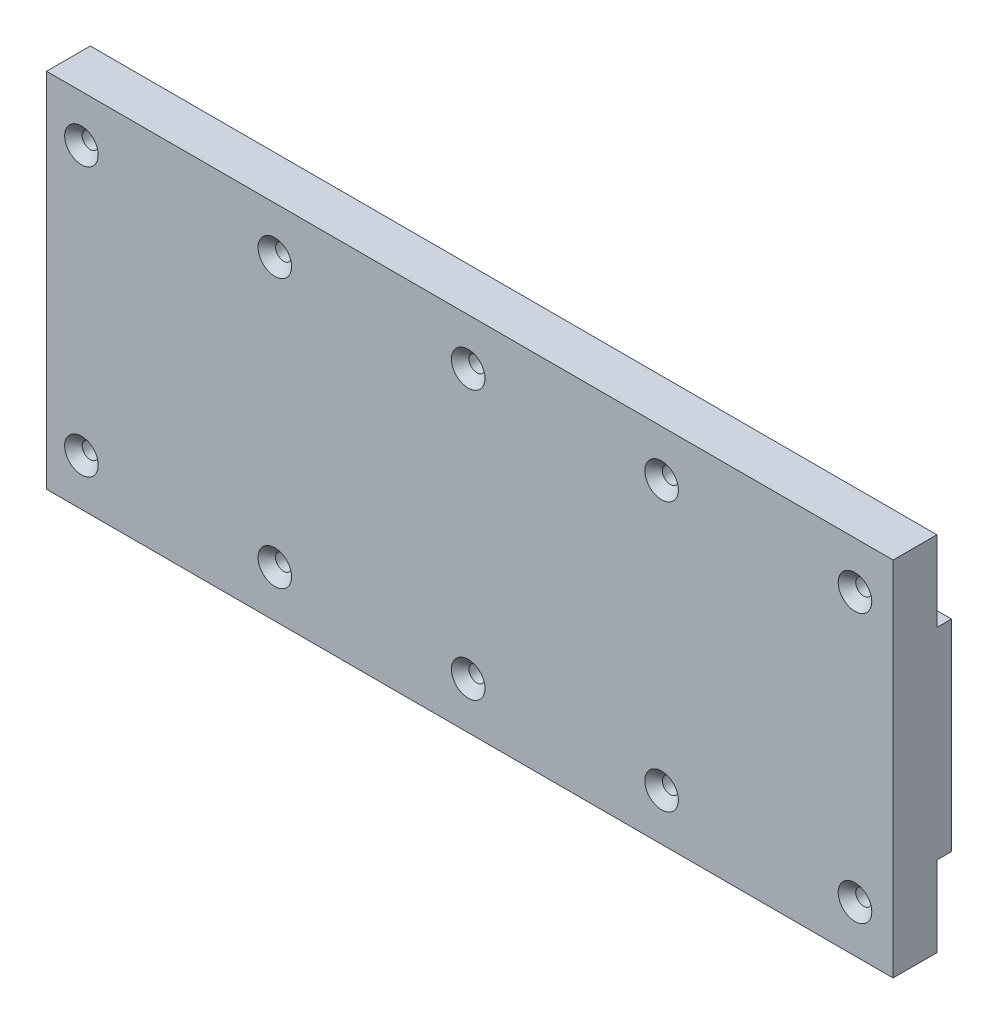
SolidWorks part; units mm, degrees
ref_plane "Front Plane" through (0, 0, 0) normal (0, 0, 1) x (1, 0, 0)
ref_plane "Top Plane" through (0, 0, 0) normal (0, 1, 0) x (1, 0, 0)
ref_plane "Right Plane" through (0, 0, 0) normal (1, 0, 0) x (0, 0, -1)
sketch "Sketch1" plane through (0, 0, 0) normal (1, 0, 0) x (0, 0, -1)
  line L1 (0, 0) -> (40, 0)
  line L2 (0, 0) -> (0, 248)
  line L3 (0, 248) -> (40, 248)
  line L4 (40, 0) -> (40, 248)
  dimension "D1" = 40
  dimension "D2" = 248
extrude "Boss-Extrude1" add sketch "Sketch1" against normal blind 580
sketch "Sketch2" plane through (0, 0, 0) normal (1, 0, 0) x (0, 0, -1)
  line L0 (40, 193) -> (30, 193)
  line L2 (40, 55) -> (40, 0)
  line L4 (40, 0) -> (30, 0)
  line L5 (30, 248) -> (40, 248)
  line L7 (40, 0) -> (40, 248) construction
  line L8 (40, 248) -> (40, 193)
  line L9 (30, 55) -> (40, 55)
  line L10 (30, 193) -> (30, 248)
  line L11 (40, 248) -> (0, 248) construction
  line L12 (30, 55) -> (30, 0)
  line L13 (0, 0) -> (40, 0) construction
extrude "Cut-Extrude1" cut sketch "Sketch2" against normal through all
sketch "Sketch3" plane through (0, 0, 0) normal (0, 0, 1) x (1, 0, 0)
  line L2 (-580, 124) -> (-142.5576, 124) construction
  line L3 (-580, 248) -> (-580, 0) construction
  line L4 (-580, 216) -> (-580, 32)
  circle A0 centre (-556.0954, 32) radius 6
  circle A1 centre (-556.0954, 216) radius 6
  circle A2 centre (-556.0954, 32) radius 5.5
  circle A3 centre (-556.0954, 216) radius 5.5
  circle A4 centre (-423.5954, 32) radius 5.5
  circle A5 centre (-291.0954, 32) radius 5.5
  circle A6 centre (-158.5954, 32) radius 5.5
  circle A7 centre (-26.0954, 32) radius 5.5
  circle A8 centre (-423.5954, 216) radius 5.5
  circle A9 centre (-291.0954, 216) radius 5.5
  circle A10 centre (-158.5954, 216) radius 5.5
  circle A11 centre (-26.0954, 216) radius 5.5
  dimension "D2" = 11
  dimension "D1" = 92
  dimension "D3" = 5
  dimension "D4" = 5
extrude "Cut-Extrude2" cut sketch "Sketch3" against normal through all contours A2 | A4 | A5 | A6 | A7 | A11 | A10 | A9 | A8 | A3
chamfer "Chamfer1" distance 6 angle 45 10 edges at (-550.5954, 216, 0) (-418.0954, 216, 0) (-285.5954, 216, 0) (-153.0954, 216, 0) (-20.5954, 216, 0) (-20.5954, 32, 0) (-153.0954, 32, 0) (-285.5954, 32, 0) (-418.0954, 32, 0) (-550.5954, 32, 0)
